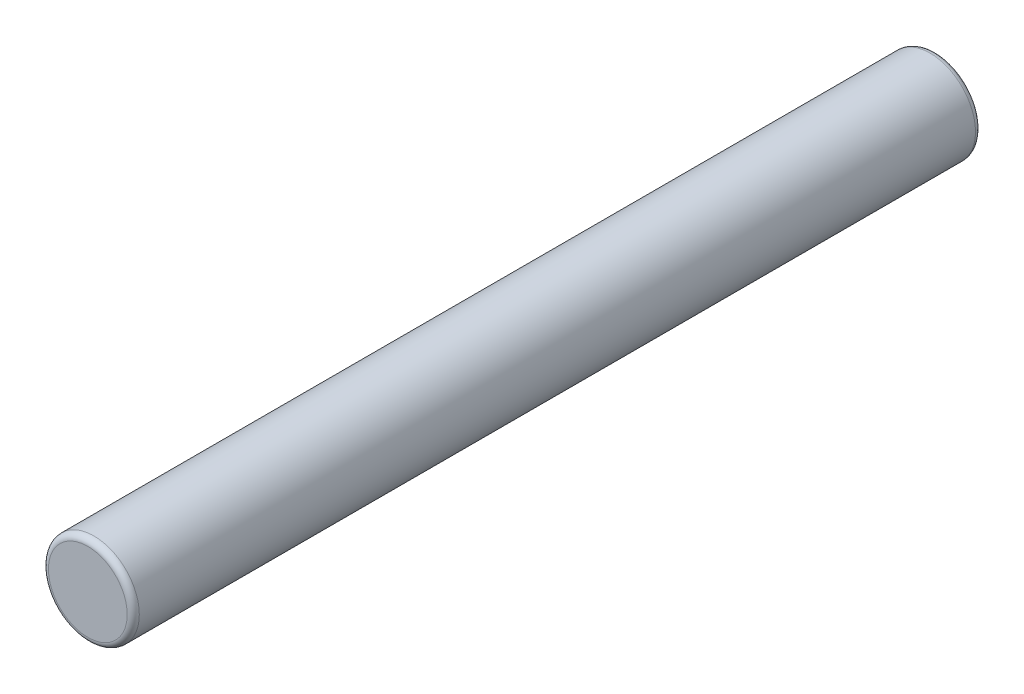
SolidWorks part; units mm, degrees
ref_plane "Front Plane" through (0, 0, 0) normal (0, 0, 1) x (1, 0, 0)
ref_plane "Top Plane" through (0, 0, 0) normal (0, 1, 0) x (1, 0, 0)
ref_plane "Right Plane" through (0, 0, 0) normal (1, 0, 0) x (0, 0, -1)
sketch "Sketch1" plane through (0, 0, 0) normal (0, 0, 1) x (1, 0, 0)
  circle A0 centre (0, 0) radius 0.75
  dimension "D1" = 1.5
extrude "Extrude1" add sketch "Sketch1" along normal blind 14
fillet "Fillet1" radius 0.1 2 edges at (0.75, 0, 0) (0.75, 0, 14)
